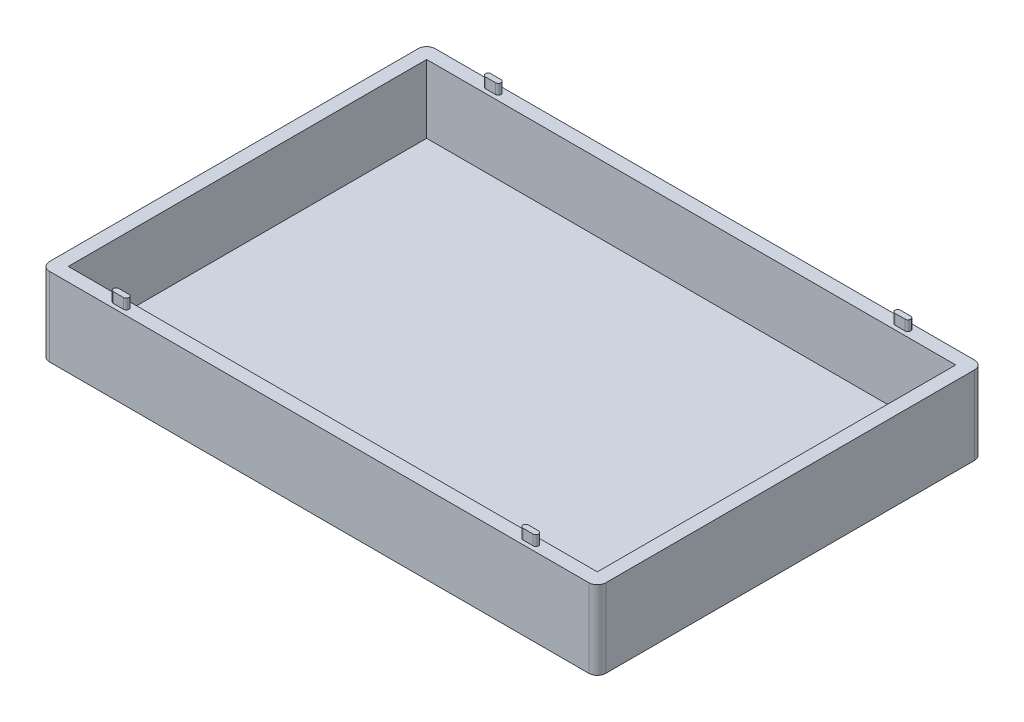
SolidWorks part; units mm, degrees
ref_plane "Front Plane" through (0, 0, 0) normal (0, 0, 1) x (1, 0, 0)
ref_plane "Top Plane" through (0, 0, 0) normal (0, 1, 0) x (1, 0, 0)
ref_plane "Right Plane" through (0, 0, 0) normal (1, 0, 0) x (0, 0, -1)
sketch "Sketch1" plane through (0, 0, 0) normal (0, 1, 0) x (1, 0, 0)
  line L1 (-81.5, 56.5) -> (81.5, 56.5)
  line L2 (-81.5, 56.5) -> (-81.5, -56.5)
  line L3 (-81.5, -56.5) -> (81.5, -56.5)
  line L4 (81.5, 56.5) -> (81.5, -56.5)
  line L5 (-81.5, 56.5) -> (81.5, -56.5) construction
  line L6 (-81.5, -56.5) -> (81.5, 56.5) construction
  point P0 (0, 0)
  dimension "D1" = 113
  dimension "D2" = 163
extrude "OuterCut" add sketch "Sketch1" along normal blind 23
fillet "Fillet2" radius 2.5 1 edges at (81.5, 11.5, 56.5)
fillet "Fillet3" radius 2.5 3 edges at (81.5, 11.5, -56.5) (-81.5, 11.5, -56.5) (-81.5, 11.5, 56.5)
sketch "Sketch2" plane through (0, 23, 0) normal (0, 1, 0) x (1, 0, 0)
  line L1 (77.5, -52.5) -> (-77.5, -52.5)
  line L2 (77.5, -52.5) -> (77.5, 52.5)
  line L3 (77.5, 52.5) -> (-77.5, 52.5)
  line L4 (-77.5, -52.5) -> (-77.5, 52.5)
  line L5 (77.5, -52.5) -> (-77.5, 52.5) construction
  line L6 (77.5, 52.5) -> (-77.5, -52.5) construction
  point P0 (0, 0)
  dimension "D1" = 105
  dimension "D2" = 155
extrude "InnerCut" cut sketch "Sketch2" against normal blind 20 contours L1 L4 L3 L2
sketch "Sketch9" plane through (0, 23, 0) normal (0, 1, 0) x (1, 0, 0)
  line L0 (58.5, -54.5) -> (61.5, -54.5) construction
  line L1 (58.5, -53.7) -> (61.5, -53.7)
  line L2 (58.5, -55.3) -> (61.5, -55.3)
  line L3 (77.5, -52.5) -> (-77.5, -52.5) construction
  line L4 (81.5, -54) -> (81.5, 54) construction
  line L5 (-61.5, -54.5) -> (-58.5, -54.5) construction
  line L6 (-61.5, -53.7) -> (-58.5, -53.7)
  line L7 (-61.5, -55.3) -> (-58.5, -55.3)
  line L8 (-81.5, 54) -> (-81.5, -54) construction
  line L9 (-61.5, 54.5) -> (-58.5, 54.5) construction
  line L10 (-61.5, 55.3) -> (-58.5, 55.3)
  line L11 (-61.5, 53.7) -> (-58.5, 53.7)
  line L12 (79, 56.5) -> (-79, 56.5) construction
  line L14 (58.5, 54.5) -> (61.5, 54.5) construction
  line L15 (58.5, 55.3) -> (61.5, 55.3)
  line L16 (58.5, 53.7) -> (61.5, 53.7)
  arc A0 (58.5, -53.7) -> (58.5, -55.3) centre (58.5, -54.5) ccw
  arc A1 (61.5, -55.3) -> (61.5, -53.7) centre (61.5, -54.5) ccw
  arc A2 (-61.5, -53.7) -> (-61.5, -55.3) centre (-61.5, -54.5) ccw
  arc A3 (-58.5, -55.3) -> (-58.5, -53.7) centre (-58.5, -54.5) ccw
  arc A4 (-61.5, 55.3) -> (-61.5, 53.7) centre (-61.5, 54.5) ccw
  arc A5 (-58.5, 53.7) -> (-58.5, 55.3) centre (-58.5, 54.5) ccw
  arc A6 (58.5, 55.3) -> (58.5, 53.7) centre (58.5, 54.5) ccw
  arc A7 (61.5, 53.7) -> (61.5, 55.3) centre (61.5, 54.5) ccw
  point P2 (60, -54.5)
  point P13 (-60, -54.5)
  point P22 (-60, 54.5)
  point P31 (60, 54.5)
  dimension "D2" = 0.8
  dimension "D6" = 0.8
  dimension "D9" = 0.8
  dimension "D13" = 0.8
  dimension "D1" = 3
  dimension "D3" = 1.2
  dimension "D4" = 20
  dimension "D5" = 3
  dimension "D7" = 20
  dimension "D8" = 1.2
  dimension "D10" = 20
  dimension "D11" = 3
  dimension "D12" = 20
extrude "Boss-Extrude5" add sketch "Sketch9" along normal blind 3
